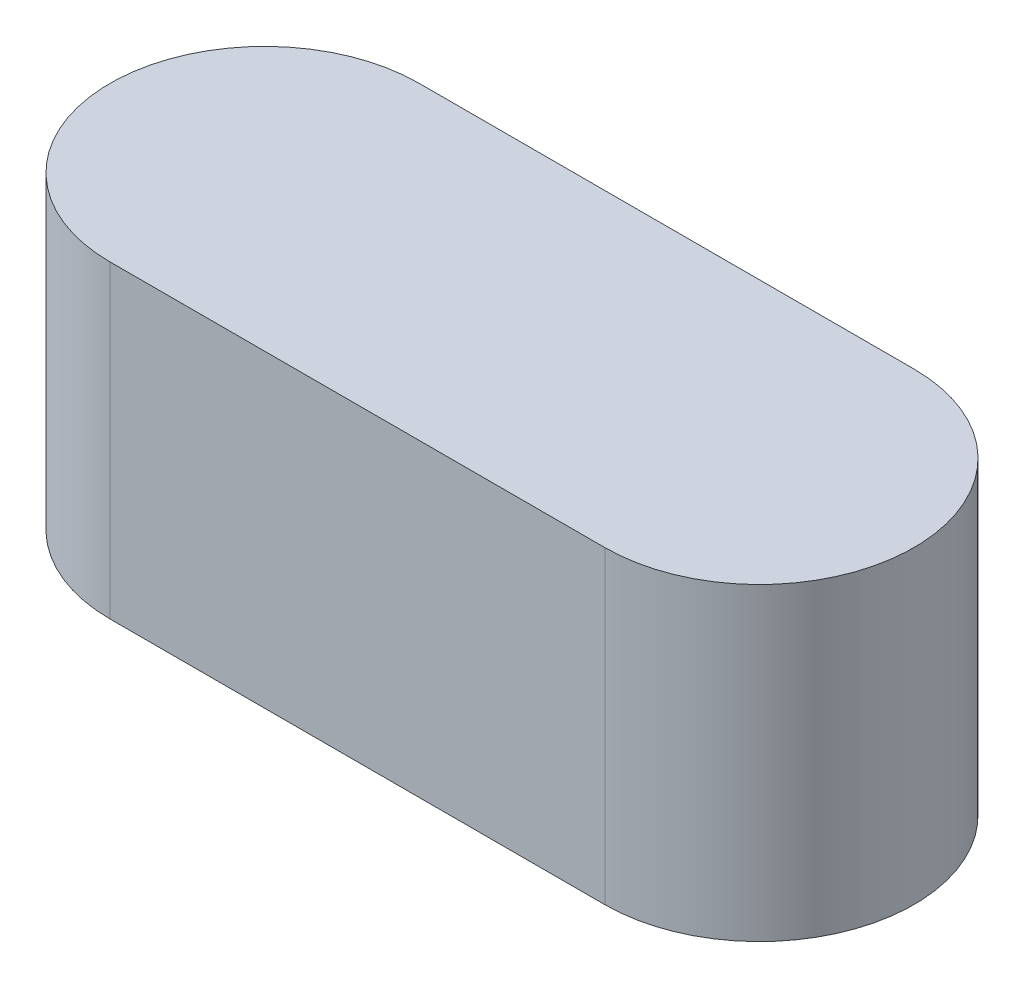
SolidWorks part; units mm, degrees
ref_plane "前视基准面" through (0, 0, 0) normal (0, 0, 1) x (1, 0, 0)
ref_plane "上视基准面" through (0, 0, 0) normal (0, 1, 0) x (1, 0, 0)
ref_plane "右视基准面" through (0, 0, 0) normal (1, 0, 0) x (0, 0, -1)
sketch "草图1" plane through (0, 0, 0) normal (0, 1, 0) x (1, 0, 0)
  line L0 (0, 0) -> (8, 0) construction
  line L1 (-55, 0) -> (55, 0) construction
  line L2 (0, 2.5) -> (8, 2.5)
  line L3 (0, -2.5) -> (8, -2.5)
  arc A0 (0, 2.5) -> (0, -2.5) centre (0, 0) ccw
  arc A1 (8, -2.5) -> (8, 2.5) centre (8, 0) ccw
  point P5 (4, 0)
  dimension "D2" = 5
  dimension "D1" = 8
extrude "凸台-拉伸1" add sketch "草图1" along normal blind 5
